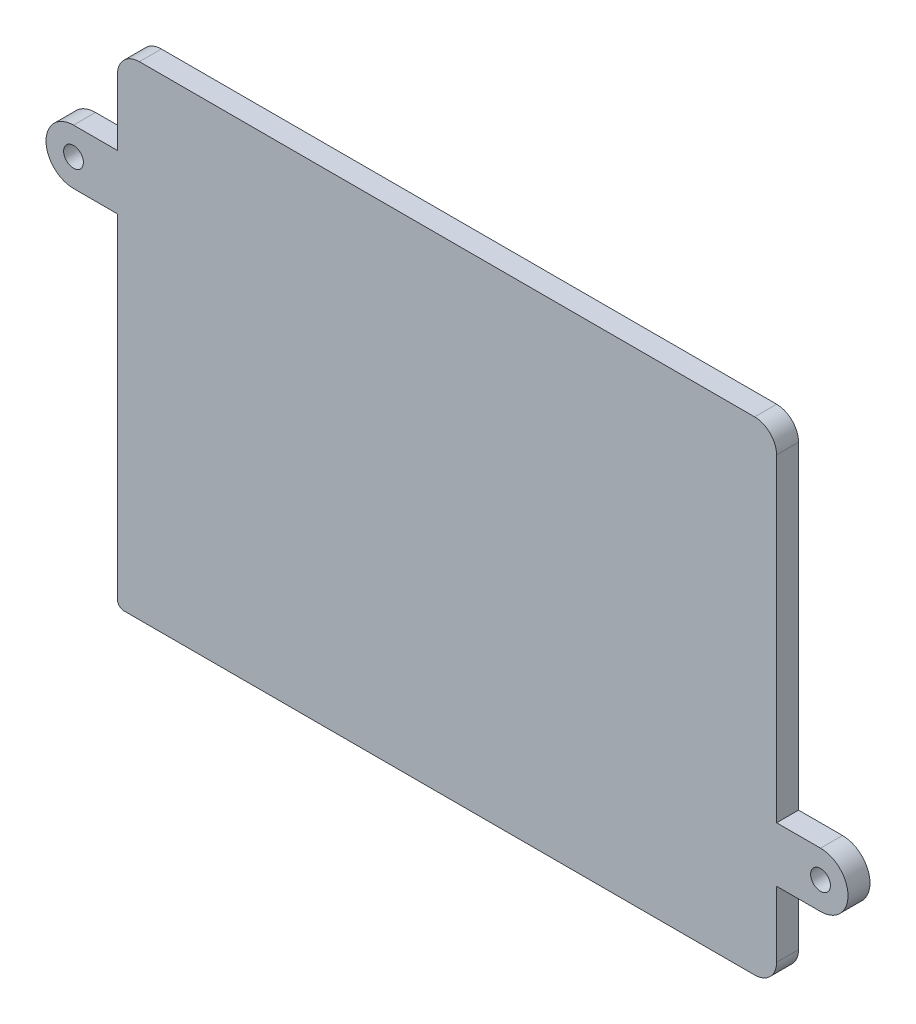
SolidWorks part; units mm, degrees
ref_plane "Front Plane" through (0, 0, 0) normal (0, 0, 1) x (1, 0, 0)
ref_plane "Top Plane" through (0, 0, 0) normal (0, 1, 0) x (1, 0, 0)
ref_plane "Right Plane" through (0, 0, 0) normal (1, 0, 0) x (0, 0, -1)
sketch "Sketch1" plane through (0, 0, 0) normal (0, 0, 1) x (1, 0, 0)
  line L0 (-85, 35) -> (-75, 35)
  line L1 (-85, 22.5) -> (-75, 22.5)
  line L2 (85, -22.5) -> (75, -22.5)
  line L3 (85, -35) -> (75, -35)
  line L4 (-75, 50) -> (-75, 35)
  line L5 (-73.5, -55) -> (70, -55)
  line L6 (75, -50) -> (75, -35)
  line L7 (70, 55) -> (-70, 55)
  line L8 (-75, 50) -> (-75, 35)
  line L9 (-73.5, -55) -> (70, -55)
  line L10 (75, -50) -> (75, -35)
  line L11 (70, 55) -> (-70, 55)
  line L36 (-75, 35) -> (-85, 35)
  line L37 (-75, 35) -> (-85, 35)
  line L38 (-85, 22.5) -> (-75, 22.5)
  line L39 (-85, 22.5) -> (-75, 22.5)
  line L40 (-75, 22.5) -> (-75, -53.5)
  line L41 (-75, 22.5) -> (-75, -53.5)
  line L42 (75, -35) -> (85, -35)
  line L43 (75, -35) -> (85, -35)
  line L44 (85, -22.5) -> (75, -22.5)
  line L45 (85, -22.5) -> (75, -22.5)
  line L46 (75, -22.5) -> (75, 50)
  line L47 (75, -22.5) -> (75, 50)
  circle A0 centre (-85, 28.75) radius 2.25
  circle A1 centre (85, -28.75) radius 2.25
  circle A2 centre (85, -28.75) radius 6.25
  circle A3 centre (-85, 28.75) radius 6.25
  arc A4 (-75, -53.5) -> (-73.5, -55) centre (-73.5, -53.5) ccw
  arc A5 (70, -55) -> (75, -50) centre (70, -50) ccw
  arc A6 (75, 50) -> (70, 55) centre (70, 50) ccw
  arc A7 (-70, 55) -> (-75, 50) centre (-70, 50) ccw
  arc A8 (-75, -53.5) -> (-73.5, -55) centre (-73.5, -53.5) ccw
  arc A9 (70, -55) -> (75, -50) centre (70, -50) ccw
  arc A10 (75, 50) -> (70, 55) centre (70, 50) ccw
  arc A11 (-70, 55) -> (-75, 50) centre (-70, 50) ccw
  arc A24 (-85, 35) -> (-85, 22.5) centre (-85, 28.75) ccw
  arc A25 (-85, 35) -> (-85, 22.5) centre (-85, 28.75) ccw
  arc A26 (85, -35) -> (85, -22.5) centre (85, -28.75) ccw
  arc A27 (85, -35) -> (85, -22.5) centre (85, -28.75) ccw
  point P26 (84.678, -35.9996)
  point P27 (85.7149, -28.1871)
  point P28 (-85.2727, 39.8169)
  dimension "D2" = 4.5
  dimension "D3" = 4.5
  dimension "D1" = 0
extrude "Boss-Extrude1" add sketch "Sketch1" along normal blind 5 contours L11 A11 L8 A8 L9 A9 L10 A10 | A3 A0 | A3 L1 L8 L0 | A2 L2 L10 L3 | A2 A1
sketch "Sketch3" plane through (0, 0, 0) normal (0, 0, -1) x (-1, 0, 0)
  line L0 (-65, 50) -> (65, 50)
  line L1 (70, 45) -> (70, -45)
  line L2 (65, -50) -> (-65, -50)
  line L3 (-70, -45) -> (-70, 45)
  line L4 (-68.5, -45) -> (-68.5, 45)
  line L5 (-65, 48.5) -> (65, 48.5)
  line L6 (68.5, 45) -> (68.5, -45)
  line L7 (65, -48.5) -> (-65, -48.5)
  arc A0 (-65, 50) -> (-70, 45) centre (-65, 45) ccw construction
  arc A1 (70, 45) -> (65, 50) centre (65, 45) ccw construction
  arc A2 (65, -50) -> (70, -45) centre (65, -45) ccw construction
  arc A3 (-70, -45) -> (-65, -50) centre (-65, -45) ccw construction
  arc A4 (-65, 50) -> (-70, 45) centre (-65, 45) ccw
  arc A5 (70, 45) -> (65, 50) centre (65, 45) ccw
  arc A6 (65, -50) -> (70, -45) centre (65, -45) ccw
  arc A7 (-70, -45) -> (-65, -50) centre (-65, -45) ccw
  arc A8 (-65, 48.5) -> (-68.5, 45) centre (-65, 45) ccw
  arc A9 (68.5, 45) -> (65, 48.5) centre (65, 45) ccw
  arc A10 (65, -48.5) -> (68.5, -45) centre (65, -45) ccw
  arc A11 (-68.5, -45) -> (-65, -48.5) centre (-65, -45) ccw
  dimension "D1" = 1.5
extrude "Boss-Extrude2" add sketch "Sketch3" along normal blind 2 contours L4 A11 L7 A10 L6 A9 L5 A8
